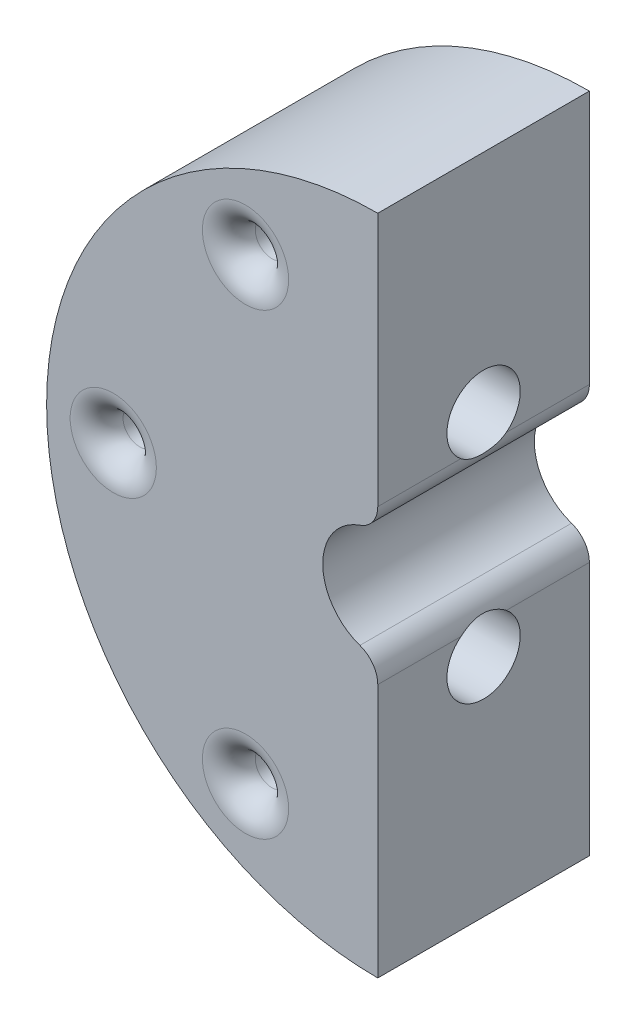
SolidWorks part; units mm, degrees
material "PBT General Purpose"
ref_plane "Front" through (0, 0, 0) normal (0, 0, 1) x (1, 0, 0)
ref_plane "Top" through (0, 0, 0) normal (0, 1, 0) x (1, 0, 0)
ref_plane "Right" through (0, 0, 0) normal (1, 0, 0) x (0, 0, -1)
sketch "Sketch1" plane through (0, 0, 0) normal (0, 0, 1) x (1, 0, 0)
  line L0 (-7.9375, 0) -> (0, 0) construction
  line L1 (-7.9375, 0) -> (-9.9375, 0) construction
  line L2 (-3.9687, 6.8741) -> (0, 0) construction
  circle A0 centre (0, 0) radius 1.651
  circle A1 centre (0, 0) radius 9.9375
  circle A2 centre (-7.9375, 0) radius 0.5
  circle A3 centre (-3.9687, 6.8741) radius 0.5
  circle A4 centre (3.9688, 6.8741) radius 0.5
  circle A5 centre (7.9375, 0) radius 0.5
  circle A6 centre (3.9688, -6.8741) radius 0.5
  circle A7 centre (-3.9688, -6.8741) radius 0.5
  dimension "D1" = 3.302
  dimension "D2" = 7.9375
  dimension "D3" = 1
  dimension "D4" = 2
  dimension "D6" = 60
  dimension "D5" = 6
extrude "Boss-Extrude1" add sketch "Sketch1" along normal blind 6.35
sketch "Sketch2" plane through (0, 0, 6.35) normal (0, 0, 1) x (1, 0, 0)
  line L0 (0, 0) -> (0, 25.4)
  line L1 (0, 25.4) -> (50.8, 25.4)
  line L2 (50.8, 25.4) -> (50.8, -25.4)
  line L3 (50.8, -25.4) -> (0, -25.4)
  line L4 (0, -25.4) -> (0, 0)
  dimension "D1" = 50.8
  dimension "D2" = 50.8
extrude "Cut-Extrude1" cut sketch "Sketch2" against normal through all
fillet "Fillet1" radius 0.7937 2 edges at (0, 1.651, 3.175) (0, -1.651, 3.175)
fillet "Fillet2" radius 0.7937 6 edges at (-3.4687, 6.8741, 0) (-3.4687, 6.8741, 6.35) (-3.4688, -6.8741, 0) (-3.4688, -6.8741, 6.35) (-7.4375, 0, 0) (-7.4375, 0, 6.35)
ref_plane "Plane1" through (-9.9375, 0, 0) normal (-1, 0, 0) x (0, 0, 1)
hole_wizard "M2 Clearance Hole1" positions "Sketch12" profile "Sketch11" hole size "M2" standard "Ansi Metric" end condition through all
sketch "Sketch12" plane through (-9.9375, 0, 0) normal (-1, 0, 0) x (0, 0, 1)
  line L0 (0, 0) -> (6.35, 0) construction
  line L1 (6.35, -9.9375) -> (6.35, 9.9375) construction
  line L3 (3.175, 3.175) -> (3.175, 0) construction
  line L4 (3.175, 0) -> (3.175, -3.175) construction
  point P1 (3.175, 3.175)
  point P3 (3.175, -3.175)
  dimension "D1" = 6.35
sketch "Sketch11" plane through (-9.9375, 3.175, 3.175) normal (0, 1, 0) x (0, 0, 1)
  line L0 (0, 0) -> (0, 9.9375)
  line L1 (0, 9.9375) -> (1.1, 9.9375)
  line L2 (1.1, 9.9375) -> (1.1, 0)
  line L5 (1.1, 0) -> (0, 0)
  line L11 (0, -6.35) -> (0, 107.95) construction
  dimension "Thru Hole Dia." = 2.2
  dimension "Thru Hole Depth" = 9.9375
sketch "Sketch13" plane through (-9.9375, 0, 0) normal (-1, 0, 0) x (0, 0, 1)
  line L0 (3.175, 3.175) -> (1.175, 3.175) construction
  line L1 (1.175, 4.3297) -> (1.175, 2.0203)
  line L2 (3.175, 5.4844) -> (1.175, 4.3297)
  line L3 (5.175, 4.3297) -> (3.175, 5.4844)
  line L4 (5.175, 2.0203) -> (5.175, 4.3297)
  line L5 (3.175, 0.8656) -> (5.175, 2.0203)
  line L6 (1.175, 2.0203) -> (3.175, 0.8656)
  line L7 (3.175, 5.4844) -> (3.175, 3.175) construction
  line L8 (1.175, -2.0203) -> (1.175, -4.3297)
  line L9 (3.175, -0.8656) -> (1.175, -2.0203)
  line L10 (5.175, -2.0203) -> (3.175, -0.8656)
  line L11 (5.175, -4.3297) -> (5.175, -2.0203)
  line L12 (3.175, -5.4844) -> (5.175, -4.3297)
  line L13 (1.175, -4.3297) -> (3.175, -5.4844)
  line L14 (3.175, -3.175) -> (1.175, -3.175) construction
  line L15 (3.175, -0.8656) -> (3.175, -3.175) construction
  circle A0 centre (3.175, -3.175) radius 1.1 construction
  dimension "D2" = 4
  dimension "D3" = 2
  dimension "D1" = 6
extrude "Cut-Extrude2" cut sketch "Sketch13" against normal blind 4.7625
